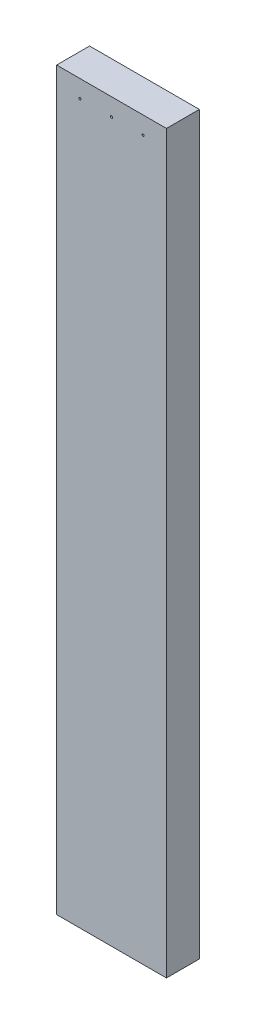
SolidWorks part; units mm, degrees
ref_plane "Front Plane" through (0, 0, 0) normal (0, 0, 1) x (1, 0, 0)
ref_plane "Top Plane" through (0, 0, 0) normal (0, 1, 0) x (1, 0, 0)
ref_plane "Right Plane" through (0, 0, 0) normal (1, 0, 0) x (0, 0, -1)
sketch "Sketch2" plane through (0, 0, 0) normal (0, 1, 0) x (1, 0, 0)
  line L0 (0, 0) -> (63.5, 19.05) construction
  line L1 (0, 0) -> (63.5, 0)
  line L2 (0, 0) -> (0, 19.05)
  line L3 (0, 19.05) -> (63.5, 19.05)
  line L4 (63.5, 0) -> (63.5, 19.05)
  circle A0 centre (31.75, 9.525) radius 3.9335 construction
  point P5 (31.75, 9.525)
  point P8 (0, 0)
  dimension "D1" = 63.5
  dimension "D2" = 19.05
extrude "Boss-Extrude1" add sketch "Sketch2" along normal blind 425.45
sketch "Sketch3" plane through (0, 0, 0) normal (0, -1, 0) x (1, 0, 0)
  line L0 (13.4874, -9.525) -> (50.0126, -9.525) construction
  circle A0 centre (13.4874, -9.525) radius 3.2004 construction
  circle A1 centre (13.4874, -9.525) radius 3.2004 construction
  circle A2 centre (13.4874, -9.525) radius 0.635
  circle A3 centre (31.75, -9.525) radius 0.635
  circle A4 centre (50.0126, -9.525) radius 0.635
  point P3 (31.75, -9.525)
  dimension "D1" = 1.27
extrude "Cut-Extrude1" cut sketch "Sketch3" against normal blind 50.8 and the other way through all
sketch "Sketch4" plane through (0, 0, 0) normal (0, 0, 1) x (1, 0, 0)
  line L0 (0, 415.29) -> (63.5, 415.29) construction
  line L1 (0, 425.45) -> (0, 0) construction
  line L2 (63.5, 425.45) -> (63.5, 0) construction
  line L4 (0, 425.45) -> (63.5, 425.45) construction
  line L5 (31.75, 415.29) -> (31.75, 396.9743) construction
  line L9 (50.0126, 0) -> (50.0126, 415.29) construction
  circle A1 centre (31.75, 415.29) radius 0.635
  circle A3 centre (50.0126, 415.29) radius 0.635
  circle A4 centre (13.4874, 415.29) radius 0.635
  point P18 (50.0126, 0)
  dimension "D2" = 1.27
  dimension "D1" = 10.16
extrude "Cut-Extrude2" cut sketch "Sketch4" against normal through all
